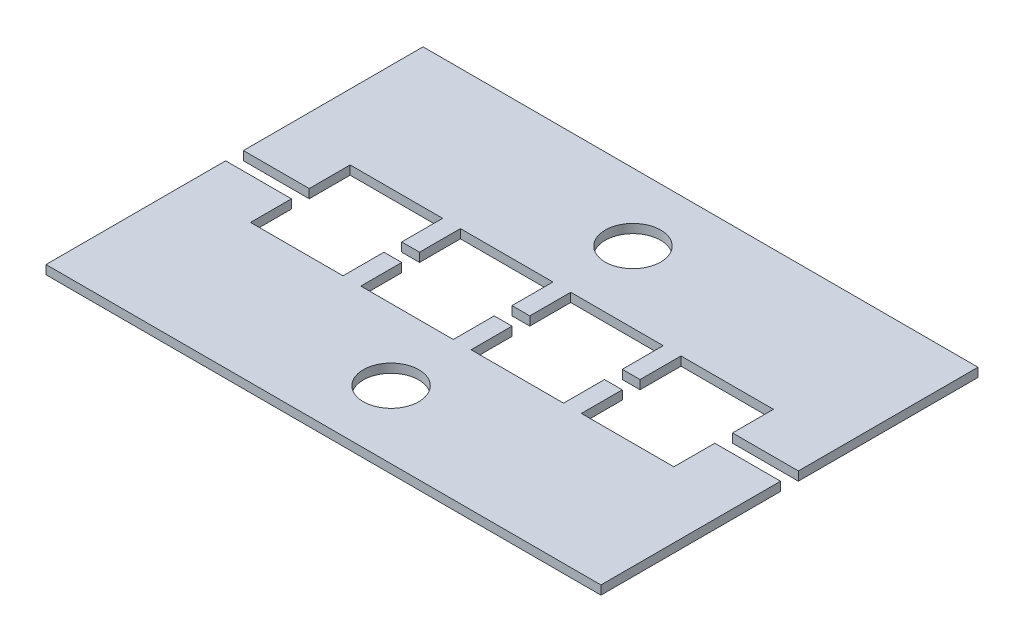
SolidWorks part; units mm, degrees
ref_plane "Front Plane" through (0, 0, 0) normal (0, 0, 1) x (1, 0, 0)
ref_plane "Top Plane" through (0, 0, 0) normal (0, 1, 0) x (1, 0, 0)
ref_plane "Right Plane" through (0, 0, 0) normal (1, 0, 0) x (0, 0, -1)
sketch "Sketch2" plane through (0, 0, 0) normal (0, 1, 0) x (1, 0, 0)
  line L0 (-19.812, 0.635) -> (-15.113, 0.635)
  line L1 (19.812, -13.462) -> (-19.812, -13.462)
  line L2 (19.812, -13.462) -> (19.812, 13.462)
  line L3 (19.812, 13.462) -> (-19.812, 13.462)
  line L4 (-19.812, -13.462) -> (-19.812, 13.462)
  line L5 (19.812, -13.462) -> (-19.812, 13.462) construction
  line L6 (19.812, 13.462) -> (-19.812, -13.462) construction
  line L7 (-19.812, -0.635) -> (-15.113, -0.635)
  line L8 (-19.812, 0) -> (19.812, 0) construction
  line L9 (-15.113, 3.556) -> (-8.509, 3.556)
  line L10 (-15.113, -3.556) -> (-8.509, -3.556)
  line L11 (0, 13.462) -> (0, -13.462) construction
  line L12 (-15.113, 3.556) -> (-15.113, -3.556)
  line L13 (-8.509, 3.556) -> (-8.509, 0.635)
  line L14 (-7.239, 3.556) -> (-7.239, 0.635)
  line L15 (-0.635, 3.556) -> (-0.635, 0.635)
  line L16 (0.635, 3.556) -> (0.635, 0.635)
  line L17 (7.239, 3.556) -> (7.239, 0.635)
  line L18 (8.509, 3.556) -> (8.509, 0.635)
  line L19 (15.113, 3.556) -> (15.113, -3.556)
  line L20 (-7.239, -3.556) -> (-0.635, -3.556)
  line L21 (-7.239, 3.556) -> (-0.635, 3.556)
  line L22 (-8.509, -0.635) -> (-7.239, -0.635)
  line L23 (-8.509, 0.635) -> (-7.239, 0.635)
  line L24 (-0.635, 0.635) -> (0.635, 0.635)
  line L25 (-0.635, -0.635) -> (0.635, -0.635)
  line L26 (-7.239, -0.635) -> (-7.239, -3.556)
  line L27 (-8.509, -0.635) -> (-8.509, -3.556)
  line L28 (-0.635, -0.635) -> (-0.635, -3.556)
  line L29 (7.239, 0.635) -> (8.509, 0.635)
  line L30 (0.635, -0.635) -> (0.635, -3.556)
  line L31 (7.239, -0.635) -> (8.509, -0.635)
  line L32 (0.635, 3.556) -> (7.239, 3.556)
  line L33 (0.635, -3.556) -> (7.239, -3.556)
  line L34 (8.509, -3.556) -> (15.113, -3.556)
  line L35 (7.239, -0.635) -> (7.239, -3.556)
  line L36 (8.509, -0.635) -> (8.509, -3.556)
  line L37 (15.113, -0.635) -> (19.812, -0.635)
  line L38 (15.113, 0.635) -> (19.812, 0.635)
  line L39 (8.509, 3.556) -> (15.113, 3.556)
  circle A0 centre (0, 8.636) radius 1.9812
  circle A1 centre (0, -8.636) radius 1.9812
  point P0 (0, 0)
  dimension "D7" = 3.9624
  dimension "D8" = 3.9624
  dimension "D1" = 26.924
  dimension "D2" = 39.624
  dimension "D3" = 0.635
  dimension "D4" = 0.635
  dimension "D5" = 3.556
  dimension "D6" = 3.556
  dimension "D9" = 17.272
  dimension "D10" = 8.636
  dimension "D11" = 0.635
  dimension "D12" = 0.635
  dimension "D13" = 1.27
  dimension "D14" = 6.604
  dimension "D15" = 6.604
  dimension "D16" = 1.27
  dimension "D17" = 6.604
  dimension "D18" = 6.604
extrude "Boss-Extrude1" add sketch "Sketch2" along normal blind 0.635 contours L18 L39 L19 L38 L2 L3 L4 L0 L12 L9 L13 L23 L14 L21 L15 L24 L16 L32 L17 L29 A0 | L37 L19 L34 L36 L31 L35 L33 L30 L25 L28 L20 L26 L22 L27 L10 L12 L7 L4 L1 L2 A1
